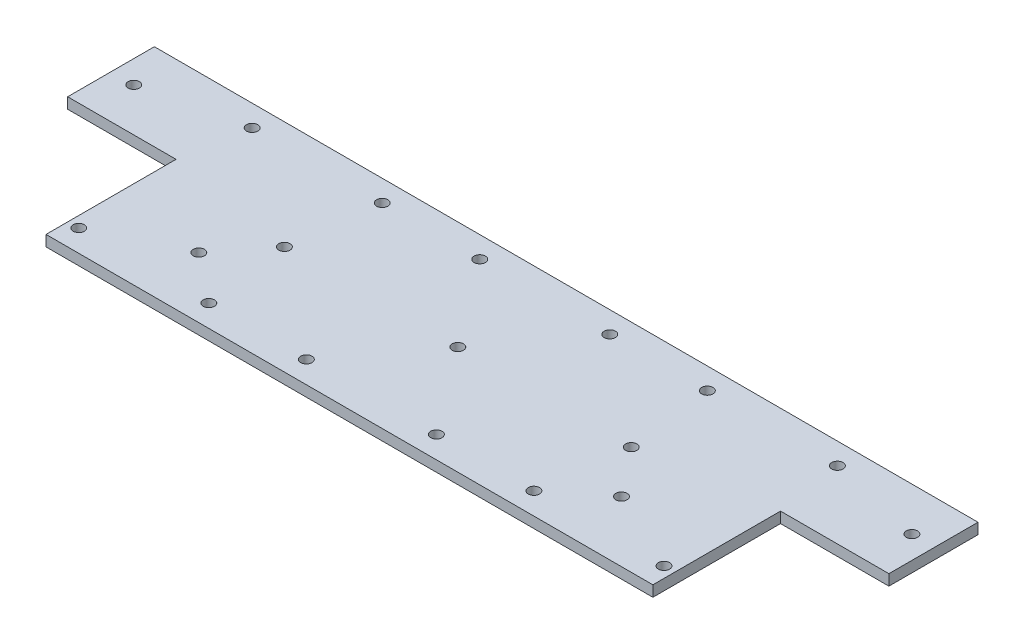
SolidWorks part; units mm, degrees
material "ABS"
ref_plane "Front Plane" through (0, 0, 0) normal (0, 0, 1) x (1, 0, 0)
ref_plane "Top Plane" through (0, 0, 0) normal (0, 1, 0) x (1, 0, 0)
ref_plane "Right Plane" through (0, 0, 0) normal (1, 0, 0) x (0, 0, -1)
sketch "Sketch4" plane through (0, 0, 0) normal (0, 1, 0) x (1, 0, 0)
  line L0 (-113.1562, 0) -> (128.1438, 0)
  line L1 (128.1438, 0) -> (128.1438, -26.1034)
  line L2 (128.1438, -26.1034) -> (96.3938, -26.1034)
  line L3 (96.3938, -26.1034) -> (96.3938, -63.5)
  line L4 (96.3938, -63.5) -> (-81.4062, -63.5)
  line L5 (-81.4062, -63.5) -> (-81.4062, -25.4)
  line L6 (-81.4062, -25.4) -> (-113.1562, -25.4)
  line L7 (-113.1562, -25.4) -> (-113.1562, 0)
  dimension "D1" = 241.3
  dimension "D2" = 177.8
  dimension "D3" = 31.75
  dimension "D4" = 38.1
  dimension "D5" = 25.4
extrude "Boss-Extrude2" add sketch "Sketch4" along normal blind 3.175
sketch "Sketch5" plane through (0, 3.175, 0) normal (0, 1, 0) x (1, 0, 0)
  line L0 (96.3938, -63.5) -> (96.3938, -26.1034) construction
  line L1 (-81.4062, -63.5) -> (96.3938, -63.5) construction
  circle A0 centre (7.4938, -31.75) radius 1.651
  circle A1 centre (58.2938, -31.75) radius 1.651
  circle A2 centre (-43.3062, -31.75) radius 1.651
  dimension "D1" = 3.302
  dimension "D2" = 3.302
  dimension "D3" = 3.302
  dimension "D4" = 88.9
  dimension "D5" = 31.75
  dimension "D6" = 50.8
  dimension "D7" = 50.8
extrude "Cut-Extrude3" cut sketch "Sketch5" against normal blind 3.175 contours A2 | A0 | A1
sketch "Sketch6" plane through (0, 3.175, 0) normal (0, 1, 0) x (1, 0, 0)
  line L0 (96.3938, -63.5) -> (96.3938, -26.1034) construction
  line L1 (-81.4062, -25.4) -> (-81.4062, -63.5) construction
  line L2 (-81.4062, -63.5) -> (96.3938, -63.5) construction
  circle A0 centre (69.4063, -45.72) radius 1.651
  circle A1 centre (-54.4187, -45.72) radius 1.651
  circle A2 centre (121.4763, -12.7) radius 1.651
  circle A3 centre (-106.4887, -12.7) radius 1.651
  dimension "D1" = 3.302
  dimension "D2" = 3.302
  dimension "D3" = 3.302
  dimension "D4" = 3.302
  dimension "D5" = 26.9875
  dimension "D6" = 26.9875
  dimension "D7" = 17.78
  dimension "D8" = 17.78
  dimension "D9" = 52.07
  dimension "D10" = 52.07
  dimension "D11" = 50.8
  dimension "D12" = 50.8
extrude "Cut-Extrude4" cut sketch "Sketch6" against normal blind 3.175 contours A2 | A3 | A1 | A0
sketch "Sketch7" plane through (0, 3.175, 0) normal (0, 1, 0) x (1, 0, 0)
  line L0 (96.3938, -63.5) -> (96.3938, -26.1034) construction
  line L1 (-81.4062, -63.5) -> (96.3938, -63.5) construction
  circle A0 centre (93.2188, -57.0738) radius 1.651
  circle A1 centre (55.1188, -57.0738) radius 1.651
  circle A2 centre (26.5438, -57.0738) radius 1.651
  circle A3 centre (-11.5562, -57.0738) radius 1.651
  circle A4 centre (-40.1312, -57.0738) radius 1.651
  circle A5 centre (-78.2312, -57.0738) radius 1.651
  dimension "D3" = 3.302
  dimension "D9" = 3.302
  dimension "D10" = 3.302
  dimension "D11" = 3.302
  dimension "D12" = 3.302
  dimension "D13" = 3.302
  dimension "D1" = 3.175
  dimension "D2" = 6.4262
  dimension "D4" = 41.275
  dimension "D5" = 69.85
  dimension "D6" = 107.95
  dimension "D7" = 136.525
  dimension "D8" = 174.625
extrude "Cut-Extrude5" cut sketch "Sketch7" against normal blind 3.81
sketch "Sketch8" plane through (0, 3.175, 0) normal (0, 1, 0) x (1, 0, 0)
  line L0 (128.1438, 0) -> (-113.1562, 0) construction
  line L1 (96.3938, -63.5) -> (96.3938, -26.1034) construction
  circle A0 centre (93.2188, -6.2738) radius 1.651
  circle A1 centre (55.1188, -6.2738) radius 1.651
  circle A2 centre (26.5438, -6.2738) radius 1.651
  circle A3 centre (-11.5562, -6.2738) radius 1.651
  circle A4 centre (-40.1312, -6.2738) radius 1.651
  circle A5 centre (-78.2312, -6.2738) radius 1.651
  dimension "D1" = 3.302
  dimension "D2" = 3.302
  dimension "D3" = 3.302
  dimension "D4" = 3.302
  dimension "D5" = 3.302
  dimension "D6" = 3.302
  dimension "D7" = 6.2738
  dimension "D8" = 3.175
  dimension "D9" = 41.275
  dimension "D10" = 69.85
  dimension "D11" = 107.95
  dimension "D12" = 136.525
  dimension "D13" = 174.625
extrude "Cut-Extrude6" cut sketch "Sketch8" against normal blind 3.81
